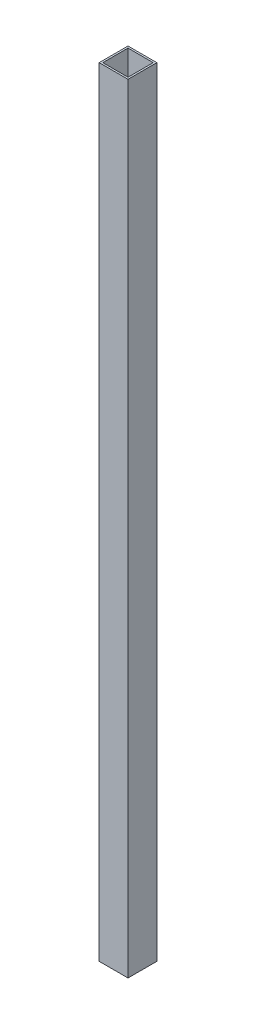
SolidWorks part; units mm, degrees
material "6061 Alloy"
ref_plane "Front Plane" through (0, 0, 0) normal (0, 0, 1) x (1, 0, 0)
ref_plane "Top Plane" through (0, 0, 0) normal (0, 1, 0) x (1, 0, 0)
ref_plane "Right Plane" through (0, 0, 0) normal (1, 0, 0) x (0, 0, -1)
sketch "Sketch1" plane through (0, 0, 0) normal (0, 1, 0) x (1, 0, 0)
  line L1 (-12.7, -12.7) -> (12.7, -12.7)
  line L2 (-12.7, -12.7) -> (-12.7, 12.7)
  line L3 (-12.7, 12.7) -> (12.7, 12.7)
  line L4 (12.7, -12.7) -> (12.7, 12.7)
  line L7 (-11.1125, -11.1125) -> (11.1125, -11.1125)
  line L8 (-11.1125, -11.1125) -> (-11.1125, 11.1125)
  line L9 (-11.1125, 11.1125) -> (11.1125, 11.1125)
  line L10 (11.1125, -11.1125) -> (11.1125, 11.1125)
  point P6 (0, 0)
  dimension "D1" = 25.4
  dimension "D2" = 25.4
  dimension "D3" = 1.5875
  dimension "D4" = 1.5875
  dimension "D5" = 1.5875
extrude "Boss-Extrude1" add sketch "Sketch1" along normal blind 685.8
